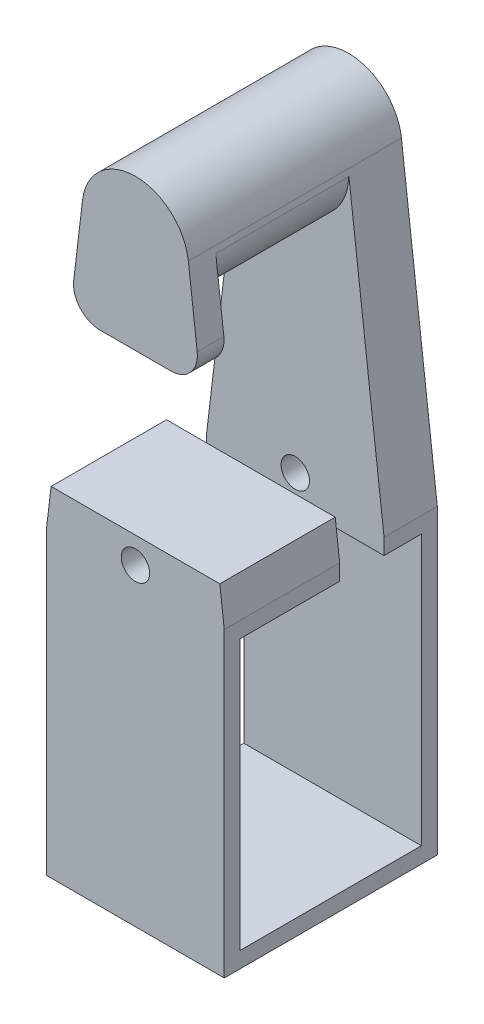
SolidWorks part; units mm, degrees
ref_plane "前视基准面" through (0, 0, 0) normal (0, 0, 1) x (1, 0, 0)
ref_plane "上视基准面" through (0, 0, 0) normal (0, 1, 0) x (1, 0, 0)
ref_plane "右视基准面" through (0, 0, 0) normal (1, 0, 0) x (0, 0, -1)
sketch "草图1" plane through (0, 0, 0) normal (0, 0, 1) x (1, 0, 0)
  line L0 (10, 0) -> (10, 85.1094) construction
  line L1 (0, 0) -> (20, 0)
  line L2 (0, 0) -> (0, 34)
  line L4 (20, 0) -> (20, 34)
  line L5 (0, 34) -> (4.0422, 67.9088)
  line L6 (20, 34) -> (15.9578, 67.9088)
  arc A0 (15.9578, 67.9088) -> (4.0422, 67.9088) centre (10, 67.1986) ccw
  dimension "D2" = 6
  dimension "D1" = 34
  dimension "D3" = 67.1986
  dimension "D4" = 20
  dimension "D5" = 34
extrude "凸台-拉伸1" add sketch "草图1" along normal blind 24
sketch "草图2" plane through (20, 0, 0) normal (1, 0, 0) x (0, 0, -1)
  line L0 (-22.2, 32.2) -> (-11, 32.2)
  line L1 (-24, 34) -> (0, 34) construction
  line L2 (-24, 34) -> (-24, 0) construction
  line L3 (-24, 0) -> (0, 0) construction
  line L4 (0, 34) -> (0, 0) construction
  line L5 (-1.8, 32.2) -> (-1.8, 1.8)
  line L6 (-22.2, 1.8) -> (-1.8, 1.8)
  line L7 (-22.2, 32.2) -> (-22.2, 1.8)
  line L19 (-24, 56.1986) -> (-24, 38.2)
  line L20 (-24, 34) -> (-24, 67.9088) construction
  line L21 (-24, 38.2) -> (-11, 38.2)
  line L22 (-6, 38.2) -> (-6, 61.1986)
  line L23 (-6, 61.1986) -> (-21, 61.1986)
  line L24 (-21, 61.1986) -> (-21, 56.1986)
  line L25 (-21, 56.1986) -> (-24, 56.1986)
  line L26 (0, 34) -> (0, 67.9088) construction
  line L27 (0, 73.1986) -> (-24, 73.1986) construction
  line L28 (-6, 32.2) -> (-1.8, 32.2)
  line L30 (-6, 38.2) -> (-6, 32.2)
  line L32 (-11, 38.2) -> (-11, 32.2)
  line L33 (-22.2, 32.2) -> (-1.8, 32.2) construction
  dimension "D2" = 6
  dimension "D3" = 6
  dimension "D4" = 12
  dimension "D5" = 3
  dimension "D6" = 5
  dimension "D7" = 5
  dimension "D1" = 1.8
extrude "切除-拉伸1" cut sketch "草图2" against normal through all
sketch "草图3" plane through (0, 0, 24) normal (0, 0, 1) x (1, 0, 0)
  line L0 (10, 38.2) -> (10, 58.1986) construction
  circle A0 centre (10, 35.2696) radius 1.6
  dimension "D1" = 3.2
extrude "切除-拉伸2" cut sketch "草图3" against normal through all
sketch "草图4" plane through (0, 0, 6) normal (0, 0, 1) x (1, 0, 0)
  line L3 (16, 67.1986) -> (19.4993, 67.1986)
  line L5 (0.5007, 38.2) -> (0.5007, 67.1986)
  line L6 (0.5007, 67.1986) -> (4, 67.1986)
  line L7 (19.4993, 38.2) -> (19.4993, 67.1986)
  line L8 (0.5007, 38.2) -> (19.4993, 38.2)
  arc A0 (4, 67.1986) -> (16, 67.1986) centre (10, 67.1986) ccw
extrude "切除-拉伸3" cut sketch "草图4" along normal up to surface (15 mm away) up to face at (10, 58.6986, 21)
fillet "圆角1" radius 3 2 edges at (17.3538, 56.1986, 22.5) (2.6462, 56.1986, 22.5)
